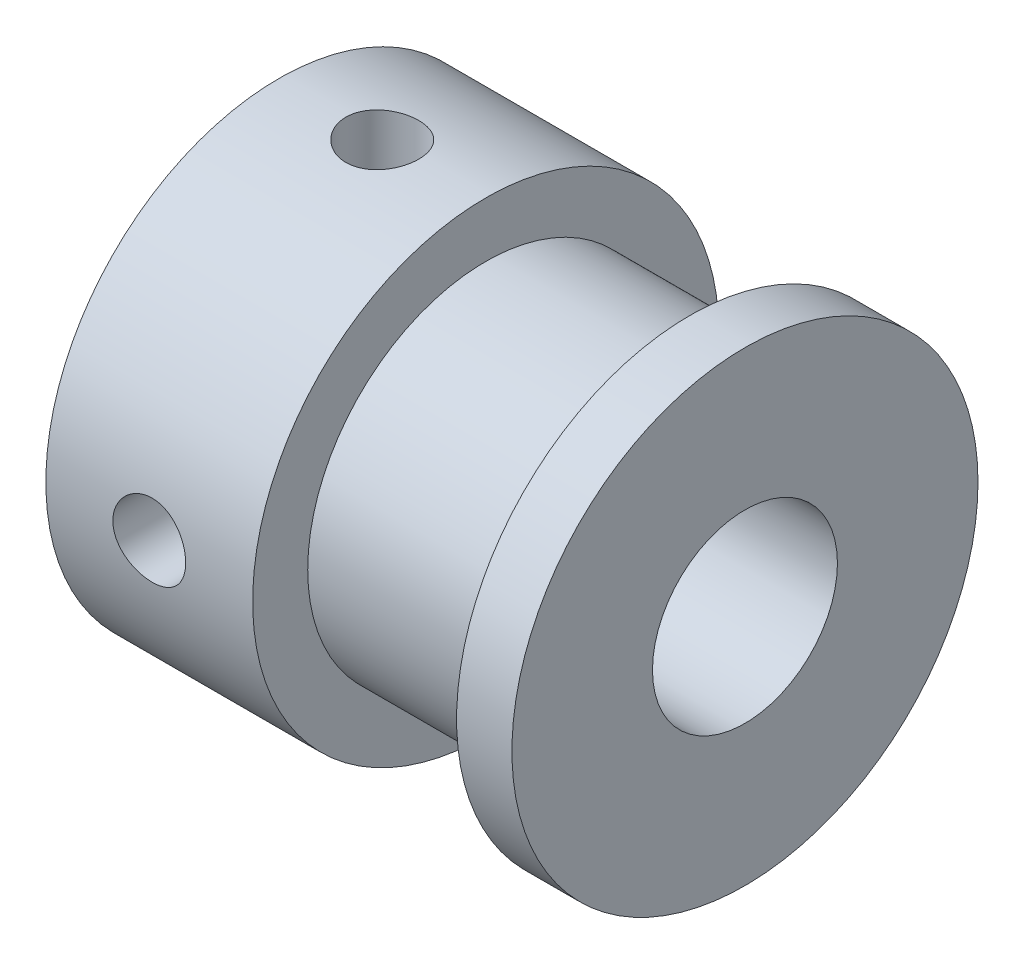
SolidWorks part; units mm, degrees
material "6061-T6 (SS)"
ref_plane "Front Plane" through (0, 0, 0) normal (0, 0, 1) x (1, 0, 0)
ref_plane "Top Plane" through (0, 0, 0) normal (0, 1, 0) x (1, 0, 0)
ref_plane "Right Plane" through (0, 0, 0) normal (1, 0, 0) x (0, 0, -1)
sketch "Sketch1" plane through (0, 0, 0) normal (0, 0, 1) x (1, 0, 0)
  line L0 (0, 3.175) -> (0, 8)
  line L1 (0, 8) -> (7.1, 8)
  line L2 (7.1, 8) -> (7.1, 6.11)
  line L3 (7.1, 6.11) -> (14.1, 6.11)
  line L4 (14.1, 6.11) -> (14.1, 8)
  line L5 (14.1, 8) -> (16, 8)
  line L6 (16, 8) -> (16, 3.175)
  line L7 (16, 3.175) -> (0, 3.175)
  line L8 (0, 0) -> (-7.6744, 0) construction
  dimension "D1" = 6.35
  dimension "D2" = 16
  dimension "D3" = 12.22
  dimension "D4" = 7.1
  dimension "D5" = 16
  dimension "D6" = 1.9
revolve "Revolve1" add sketch "Sketch1" angle 360 about L8
hole_wizard "M3x0.5 Tapped Hole1" positions "Sketch3" profile "Sketch2" tap size "M3x0.5" standard "ANSI Metric"
sketch "Sketch3" plane through (0, 0, 0) normal (0, 1, 0) x (1, 0, 0)
  line L0 (0, 0) -> (7.1, 0) construction
  line L1 (7.1, -6.11) -> (7.1, 6.11) construction
  point P8 (3.55, 0)
sketch "Sketch2" plane through (3.55, 0, 0) normal (1, 0, 0) x (0, 0, -1)
  line L0 (0, 0) -> (0, 8)
  line L1 (0, 8) -> (1.25, 8)
  line L2 (1.25, 8) -> (1.25, 0)
  line L5 (1.25, 0) -> (0, 0)
  line L11 (0, -6.35) -> (0, 107.95) construction
  dimension "Thread Major Dia." = 2.5
  dimension "Thru Tap Drill Depth" = 8
hole_wizard "M3x0.5 Tapped Hole2" positions "Sketch5" profile "Sketch4" tap size "M3x0.5" standard "ANSI Metric"
sketch "Sketch5" plane through (0, 0, 0) normal (0, 0, 1) x (1, 0, 0)
  line L0 (0, 0) -> (7.1, 0) construction
  line L1 (7.1, -6.11) -> (7.1, 6.11) construction
  point P7 (3.55, 0)
sketch "Sketch4" plane through (3.55, 0, 0) normal (1, 0, 0) x (0, 1, 0)
  line L0 (0, 0) -> (0, 8)
  line L1 (0, 8) -> (1.25, 8)
  line L2 (1.25, 8) -> (1.25, 0)
  line L5 (1.25, 0) -> (0, 0)
  line L11 (0, -6.35) -> (0, 107.95) construction
  dimension "Thread Major Dia." = 2.5
  dimension "Thru Tap Drill Depth" = 8
